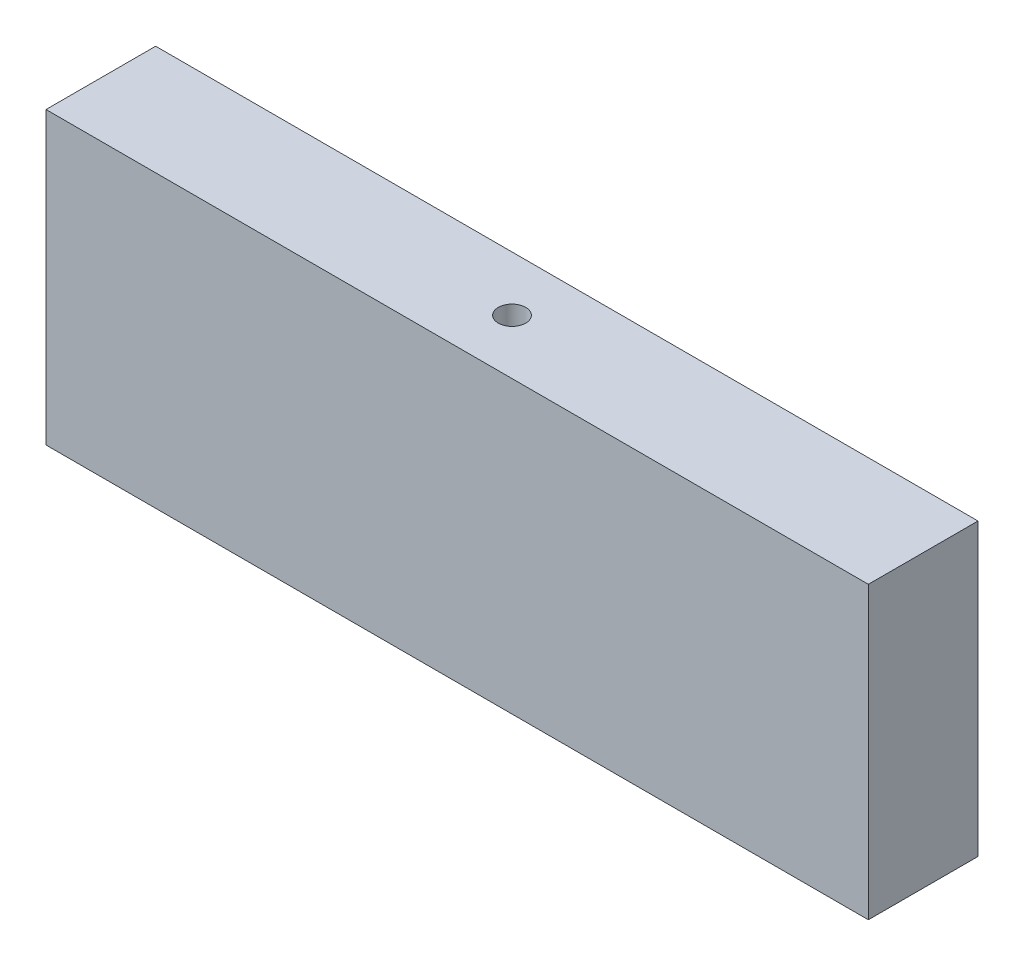
SolidWorks part; units mm, degrees
material "Кедр"
ref_plane "Спереди" through (0, 0, 0) normal (0, 0, 1) x (1, 0, 0)
ref_plane "Сверху" through (0, 0, 0) normal (0, 1, 0) x (1, 0, 0)
ref_plane "Справа" through (0, 0, 0) normal (1, 0, 0) x (0, 0, -1)
sketch "Эскиз1" plane through (0, 0, 0) normal (0, 0, 1) x (1, 0, 0)
  line L1 (-75, 26.5) -> (75, 26.5)
  line L2 (-75, 26.5) -> (-75, -26.5)
  line L3 (-75, -26.5) -> (75, -26.5)
  line L4 (75, 26.5) -> (75, -26.5)
  line L5 (-75, 26.5) -> (75, -26.5) construction
  line L6 (-75, -26.5) -> (75, 26.5) construction
  point P0 (0, 0)
  dimension "D1" = 150
  dimension "D2" = 53
extrude "Бобышка-Вытянуть1" add sketch "Эскиз1" along normal mid plane 20
sketch "Эскиз2" plane through (0, 0, 0) normal (0, 1, 0) x (1, 0, 0)
  circle A0 centre (0, 0) radius 2.5
  dimension "D1" = 5
extrude "Вырез-Вытянуть1" cut sketch "Эскиз2" against normal through all and the other way through all
